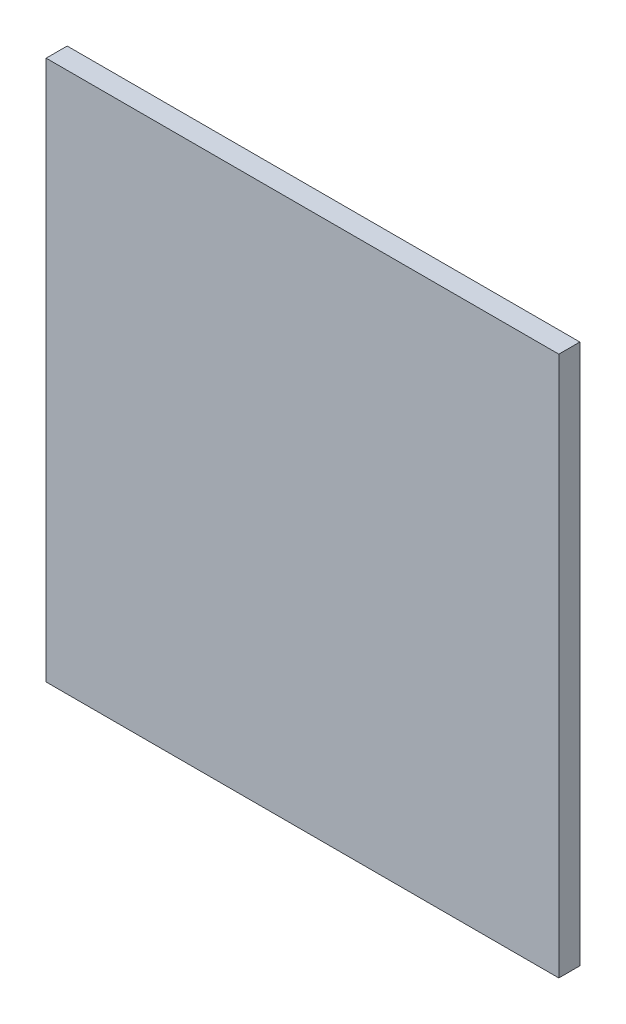
SolidWorks part; units mm, degrees
ref_plane "Front Plane" through (0, 0, 0) normal (0, 0, 1) x (1, 0, 0)
ref_plane "Top Plane" through (0, 0, 0) normal (0, 1, 0) x (1, 0, 0)
ref_plane "Right Plane" through (0, 0, 0) normal (1, 0, 0) x (0, 0, -1)
sketch "Sketch1" plane through (0, 0, 0) normal (0, 0, 1) x (1, 0, 0)
  line L1 (0, 0) -> (1096, 0)
  line L2 (0, 0) -> (0, 1155)
  line L3 (0, 1155) -> (1096, 1155)
  line L4 (1096, 0) -> (1096, 1155)
  dimension "D1" = 1155
  dimension "D2" = 1096
extrude "Boss-Extrude1" add sketch "Sketch1" along normal blind 45
